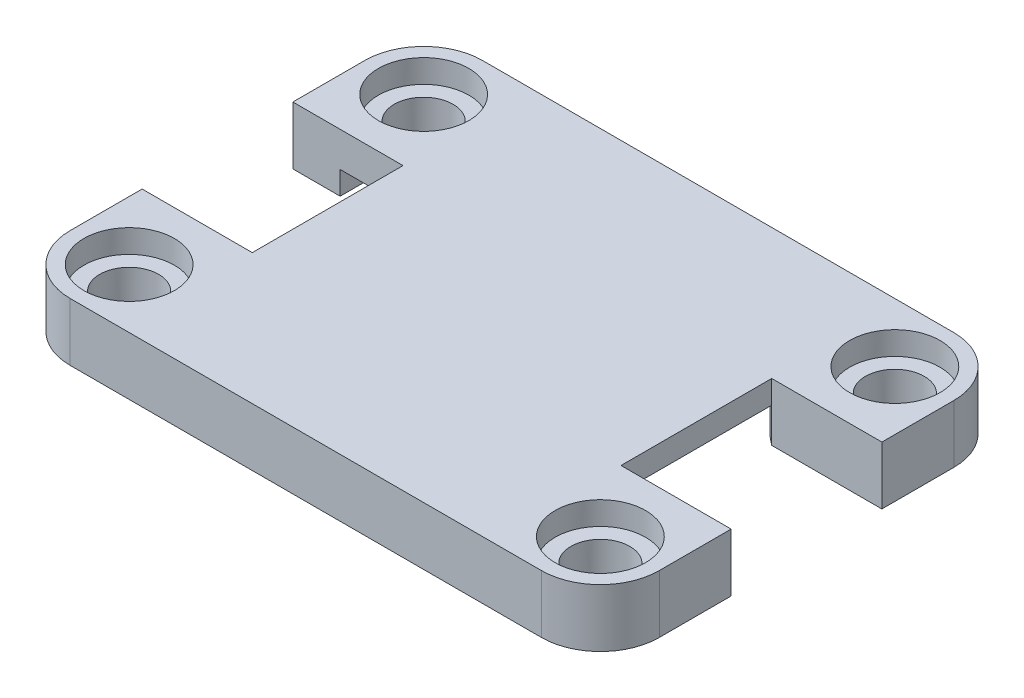
SolidWorks part; units mm, degrees
ref_plane "Front Plane" through (0, 0, 0) normal (0, 0, 1) x (1, 0, 0)
ref_plane "Top Plane" through (0, 0, 0) normal (0, 1, 0) x (1, 0, 0)
ref_plane "Right Plane" through (0, 0, 0) normal (1, 0, 0) x (0, 0, -1)
sketch "Sketch1" plane through (0, 0, 0) normal (0, 1, 0) x (1, 0, 0)
  line L0 (0, 8.89) -> (0, -8.89) construction
  line L1 (-10.16, 8.89) -> (10.16, 8.89)
  line L2 (-12.7, 6.35) -> (-12.7, -6.35)
  line L3 (-10.16, -8.89) -> (10.16, -8.89)
  line L4 (12.7, 6.35) -> (12.7, -6.35)
  line L5 (-12.7, 0) -> (12.7, 0) construction
  line L6 (-1.627, -0.635) -> (1.373, -0.635) construction
  line L7 (-1.627, 0.865) -> (1.373, 0.865) construction
  line L8 (-6.85, -6.35) -> (-6.35, -6.35) construction
  line L9 (-6.35, -6.35) -> (-3.81, -6.35) construction
  line L10 (-1.27, -6.35) -> (1.27, -6.35) construction
  line L11 (-3.81, -6.35) -> (-1.27, -6.35) construction
  line L12 (-1.627, 0.865) -> (-1.627, -2.135) construction
  line L13 (-1.627, -2.135) -> (1.373, -2.135) construction
  line L14 (1.373, 0.865) -> (1.373, -2.135) construction
  circle A0 centre (-10.16, 6.35) radius 1.27 construction
  circle A1 centre (10.16, 6.35) radius 1.27 construction
  arc A4 (10.16, 8.89) -> (12.7, 6.35) centre (10.16, 6.35) cw
  arc A5 (10.16, -8.89) -> (12.7, -6.35) centre (10.16, -6.35) ccw
  arc A6 (-12.7, -6.35) -> (-10.16, -8.89) centre (-10.16, -6.35) ccw
  arc A7 (-10.16, 8.89) -> (-12.7, 6.35) centre (-10.16, 6.35) ccw
  circle A14 centre (-1.27, -6.35) radius 0.5 construction
  circle A15 centre (-3.81, -6.35) radius 0.5 construction
  circle A16 centre (-6.35, -6.35) radius 0.5 construction
  circle A20 centre (1.27, -6.35) radius 0.5 construction
  circle A24 centre (3.81, -6.35) radius 0.5 construction
  circle A25 centre (6.35, -6.35) radius 0.5 construction
  circle A26 centre (6.35, 6.35) radius 0.5 construction
  circle A27 centre (3.81, 6.35) radius 0.5 construction
  circle A28 centre (1.27, 6.35) radius 0.5 construction
  circle A29 centre (-1.27, 6.35) radius 0.5 construction
  circle A30 centre (-3.81, 6.35) radius 0.5 construction
  circle A31 centre (-6.35, 6.35) radius 0.5 construction
  circle A32 centre (10.16, -6.35) radius 1.27 construction
  circle A33 centre (-10.16, -6.35) radius 1.27 construction
  point P51 (-0.127, -0.635)
  dimension "D1" = 25.4
  dimension "D3" = 2.54
  dimension "D5" = 1
  dimension "D2" = 17.78
  dimension "D4" = 2.54
  dimension "D6" = 3
  dimension "D7" = 12.573
  dimension "D8" = 8.255
  dimension "D9" = 0.127
  dimension "D10" = 0.635
  dimension "D11" = 2.54
extrude "Boss-Extrude1" add sketch "Sketch1" along normal blind 2.5
sketch "Sketch3" plane through (0, 2.5, 0) normal (0, 1, 0) x (1, 0, 0)
  line L0 (0, 8.89) -> (0, -8.89) construction
  line L1 (-12.7, 0) -> (12.7, 0) construction
  line L2 (-12.7, 6.35) -> (-12.7, -6.35) construction
  line L3 (12.7, -6.35) -> (12.7, 6.35) construction
  line L4 (10.16, 8.89) -> (-10.16, 8.89) construction
  line L5 (-10.16, -8.89) -> (10.16, -8.89) construction
  line L6 (7.95, 3.25) -> (7.95, -3.25)
  line L7 (-12.7, 3.25) -> (-7.95, 3.25)
  line L8 (-12.7, 3.25) -> (-12.7, -3.25)
  line L9 (-12.7, -3.25) -> (-7.95, -3.25)
  line L10 (-7.95, 3.25) -> (-7.95, -3.25)
  line L11 (12.7, -3.25) -> (7.95, -3.25)
  line L12 (12.7, 3.25) -> (12.7, -3.25)
  line L13 (12.7, 3.25) -> (7.95, 3.25)
  circle A0 centre (-10.16, 6.35) radius 1.27
  circle A1 centre (10.16, 6.35) radius 1.27
  circle A2 centre (10.16, -6.35) radius 1.27
  circle A3 centre (-10.16, -6.35) radius 1.27
  dimension "D3" = 2.54
  dimension "D1" = 6.5
  dimension "D2" = 4.75
extrude "Cut-Extrude2" cut sketch "Sketch3" against normal through all
sketch "Sketch2" plane through (0, 2.5, 0) normal (0, 1, 0) x (1, 0, 0)
  line L1 (-12.7, -3.25) -> (-7.95, -3.25) construction
  line L6 (-3.81, -5.35) -> (-3.81, -3.635)
  line L7 (-3.81, -3.635) -> (3.31, -3.635)
  line L8 (3.31, -3.635) -> (3.31, -5.35)
  line L9 (3.31, -5.35) -> (6.4866, -5.35)
  line L10 (-7.95, -5.35) -> (-3.81, -5.35)
  line L11 (6.4866, 5.35) -> (-7.95, 5.35)
  line L12 (-1.627, -2.135) -> (1.373, -2.135) construction
  line L13 (-12.7, 3.25) -> (-12.7, -3.25)
  line L14 (12.7, -3.25) -> (12.7, 3.25)
  line L15 (7.95, -3.25) -> (12.7, -3.25) construction
  line L16 (12.7, 3.25) -> (7.95, 3.25) construction
  line L17 (7.95, -3.25) -> (12.7, -3.25)
  line L18 (12.7, 3.25) -> (7.95, 3.25)
  line L19 (-12.7, -3.25) -> (-7.95, -3.25)
  line L21 (-7.95, -3.25) -> (-7.95, -5.35)
  line L23 (-7.95, 3.25) -> (-12.7, 3.25) construction
  line L24 (-7.95, 3.25) -> (-12.7, 3.25)
  line L25 (-7.95, 3.25) -> (-7.95, 5.35)
  circle A4 centre (3.81, -6.35) radius 0.5 construction
  arc A5 (7.95, 3.25) -> (6.4866, 5.35) centre (10.16, 6.35) cw
  arc A6 (7.95, -3.25) -> (6.4866, -5.35) centre (10.16, -6.35) ccw
  circle A7 centre (-10.16, -6.35) radius 1.27 construction
  dimension "D1" = 1
  dimension "D3" = 1
  dimension "D6" = 1.5
extrude "Cut-Extrude1" cut sketch "Sketch2" along normal offset from surface (4 mm away) 1 from offset 5 contours L14 L18 A5 L11 L25 L24 L13 L19 L21 L10 L6 L7 L8 L9 A6 L17
sketch "Sketch4" plane through (0, 2.5, 0) normal (0, 1, 0) x (1, 0, 0)
  circle A0 centre (-10.16, 6.35) radius 1.95
  circle A1 centre (10.16, 6.35) radius 1.95
  circle A2 centre (-10.16, -6.35) radius 1.95
  circle A3 centre (10.16, -6.35) radius 1.95
  dimension "D1" = 3.9
extrude "Cut-Extrude3" cut sketch "Sketch4" against normal offset from surface (1 mm away) 1.5 up to face at (10.16, 0, -5.08)
sketch "Sketch5" plane through (0, 2.5, 0) normal (0, 1, 0) x (1, 0, 0)
  line L1 (-7.95, 3.25) -> (-10.66, 3.25)
  line L2 (-7.95, 3.25) -> (-7.95, 4.4)
  line L3 (-7.95, 4.4) -> (-10.66, 4.4)
  line L4 (-10.66, 3.25) -> (-10.66, 4.4)
  circle A0 centre (-10.16, 6.35) radius 1.27 construction
  circle A1 centre (-10.16, 6.35) radius 1.95 construction
  dimension "D1" = 0.5
extrude "Cut-Extrude4" cut sketch "Sketch5" along normal offset from surface (3.5 mm away) 1.5 from offset 5
